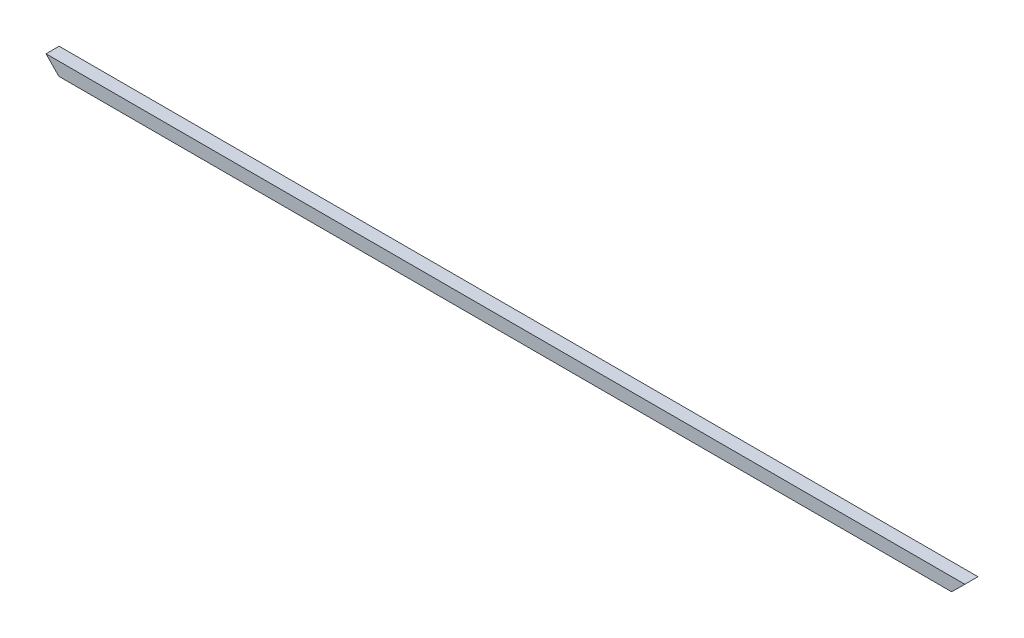
SolidWorks part; units mm, degrees
ref_plane "Front Plane" through (0, 0, 0) normal (0, 0, 1) x (1, 0, 0)
ref_plane "Top Plane" through (0, 0, 0) normal (0, 1, 0) x (1, 0, 0)
ref_plane "Right Plane" through (0, 0, 0) normal (1, 0, 0) x (0, 0, -1)
sketch "Sketch2" plane through (0, 0, 0) normal (0, 0, 1) x (1, 0, 0)
  line L0 (-2776.6507, 0) -> (23.6493, 0)
  line L1 (55, 0) -> (-55, 0) construction
  line L2 (23.6493, 0) -> (-16.7718, -40)
  line L3 (-16.7718, -40) -> (-2737.4251, -40)
  line L4 (-2737.4251, -40) -> (-2776.6507, 0)
  dimension "D1" = 45.56
  dimension "D2" = 44.7
  dimension "D3" = 2800.3
  dimension "D4" = 40
extrude "Boss-Extrude1" add sketch "Sketch2" along normal blind 40
